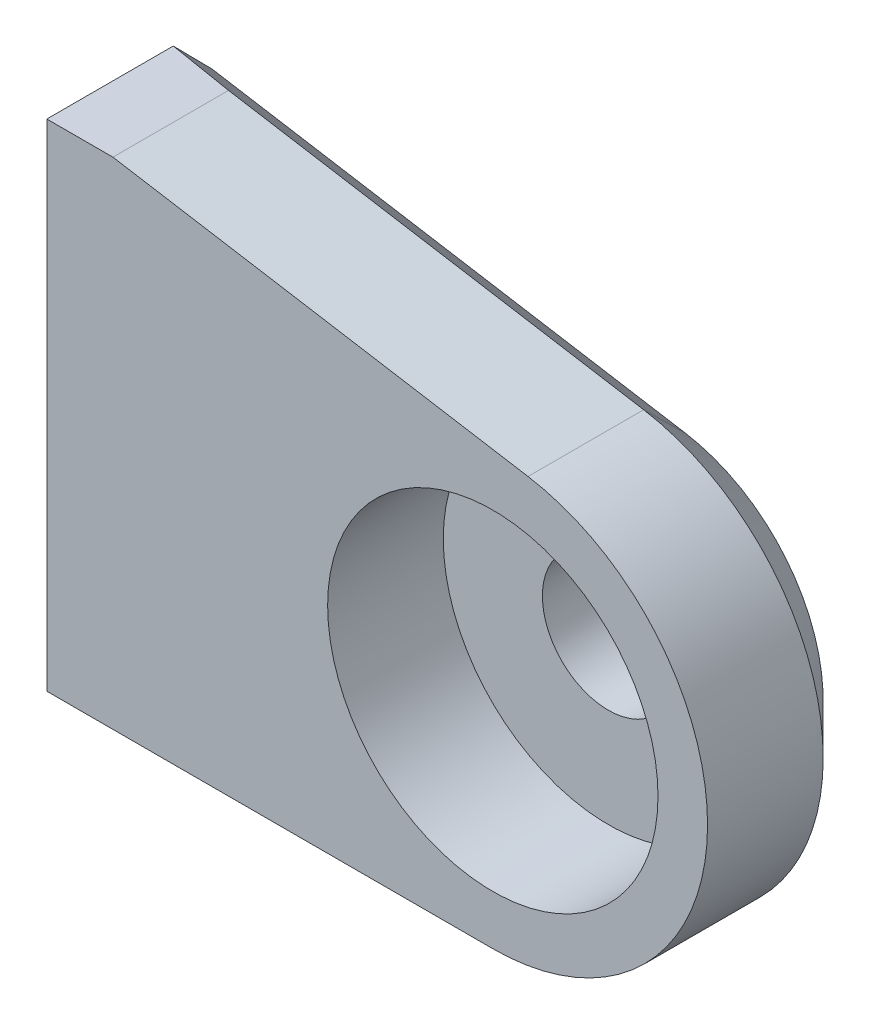
SolidWorks part; units mm, degrees
ref_plane "Front Plane" through (0, 0, 0) normal (0, 0, 1) x (1, 0, 0)
ref_plane "Top Plane" through (0, 0, 0) normal (0, 1, 0) x (1, 0, 0)
ref_plane "Right Plane" through (0, 0, 0) normal (1, 0, 0) x (0, 0, -1)
sketch "Sketch1" plane through (0, 0, 0) normal (0, 0, 1) x (1, 0, 0)
  line L0 (0, -6.5) -> (-13.5, -6.5)
  line L1 (-13.5, -6.5) -> (-13.5, 8.5)
  line L2 (-13.5, 8.5) -> (-11.5, 8.5)
  line L3 (-11.5, 8.5) -> (1.0655, 6.4121)
  arc A0 (0, -6.5) -> (1.0655, 6.4121) centre (0, 0) ccw
  circle A1 centre (0, 0) radius 2
  dimension "D3" = 6.5
  dimension "D5" = 4
  dimension "D1" = 2
  dimension "D2" = 13.5
  dimension "D4" = 15
extrude "Boss-Extrude1" add sketch "Sketch1" along normal blind 5
sketch "Sketch2" plane through (0, 0, 5) normal (0, 0, 1) x (1, 0, 0)
  circle A0 centre (0, 0) radius 5
  dimension "D1" = 10
extrude "Cut-Extrude1" cut sketch "Sketch2" against normal blind 3.5
sketch "Sketch3" plane through (-13.5, 0, 0) normal (-1, 0, 0) x (0, 0, 1)
  line L0 (2.5, 8.5) -> (2.5, -6.5) construction
  line L1 (5, 8.5) -> (0, 8.5) construction
  line L2 (5, -6.5) -> (0, -6.5) construction
  line L3 (5, 1) -> (0, 1) construction
  line L4 (5, 8.5) -> (5, -6.5) construction
  line L5 (0, 8.5) -> (0, -6.5) construction
  circle A0 centre (2.5, 6) radius 1
  circle A1 centre (2.5, -4) radius 1
  dimension "D2" = 2
  dimension "D1" = 10
extrude "Cut-Extrude2" cut sketch "Sketch3" against normal blind 2
chamfer "Chamfer1" distance 1.5 angle 45 3 edges at (-5.2173, 7.456, 0) (6.478, -0.5345, 0) (-6.75, -6.5, 0)
